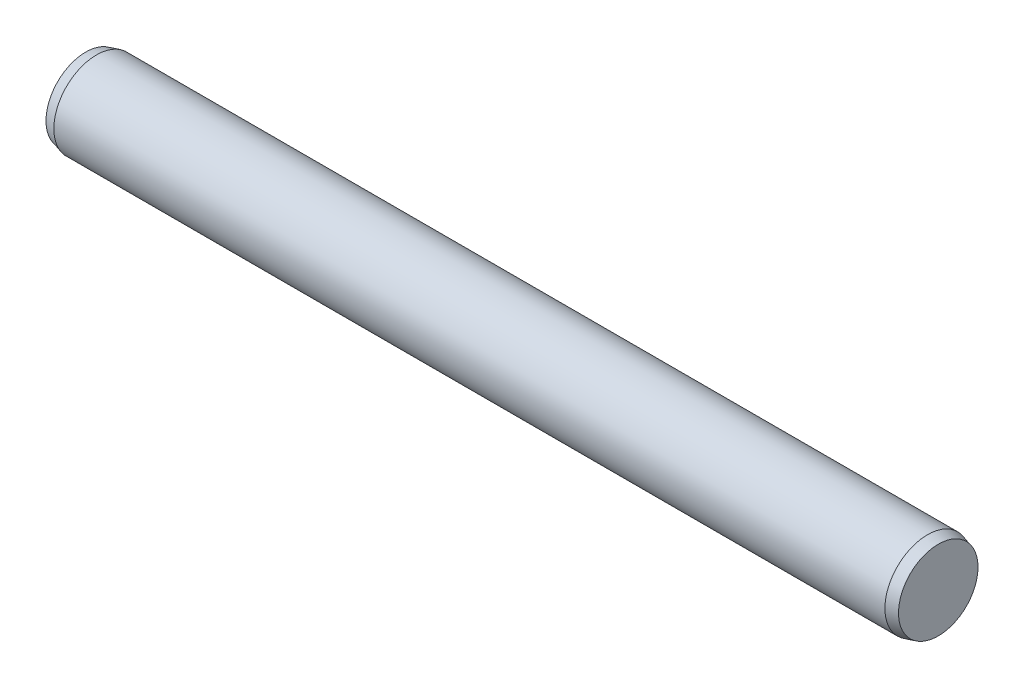
SolidWorks part; units mm, degrees
material "Stainless Steel (ferritic)"
ref_plane "Front Plane" through (0, 0, 0) normal (0, 0, 1) x (1, 0, 0)
ref_plane "Top Plane" through (0, 0, 0) normal (0, 1, 0) x (1, 0, 0)
ref_plane "Right Plane" through (0, 0, 0) normal (1, 0, 0) x (0, 0, -1)
sketch "Sketch1" plane through (0, 0, 0) normal (0, 0, 1) x (1, 0, 0)
  line L0 (-24.37, 0) -> (24.37, 0) construction
  line L1 (24.37, 2.5) -> (24.37, -2.5) construction
  line L2 (-24.37, 2.5) -> (-24.37, -2.5) construction
  line L3 (25, 2.5) -> (25, -2.5) construction
  line L4 (-25, 2.5) -> (-25, -2.5) construction
  line L5 (-24.37, 0) -> (-25, 0) construction
  line L6 (24.37, 0) -> (25, 0) construction
  dimension "Dia" = 5
  dimension "C" = 0.63
  dimension "D1" = 0.63
  dimension "Length" = 50
sketch "Sketch2" plane through (0, 0, 0) normal (1, 0, 0) x (0, 0, -1)
  circle A0 centre (0, 0) radius 2.5
extrude "Extrude1" add sketch "Sketch2" against normal up to vertex (24.37 mm away) and the other way up to vertex (24.37 mm away) up to point (-24.37, 2.5, 0) other way up to point (24.37, 2.5, 0)
sketch "Sketch3" plane through (24.37, 0, 0) normal (1, 0, 0) x (0, 0, -1)
  circle A1 centre (0, 0) radius 2.5
  circle A2 centre (0, 0) radius 2.5
  dimension "D1" = 0
extrude "Extrude2" add sketch "Sketch3" along normal up to vertex (0.63 mm away) draft 15 up to point (25, 0, 0)
sketch "Sketch4" plane through (-24.37, 0, 0) normal (-1, 0, 0) x (0, 0, 1)
  circle A1 centre (0, 0) radius 2.5
  circle A2 centre (0, 0) radius 2.5
  dimension "D1" = 0
extrude "Extrude3" add sketch "Sketch4" along normal up to vertex (0.63 mm away) draft 15 up to point (-25, 0, 0)
equation "\"D1@Sketch1\" = \"C@Sketch1\""
